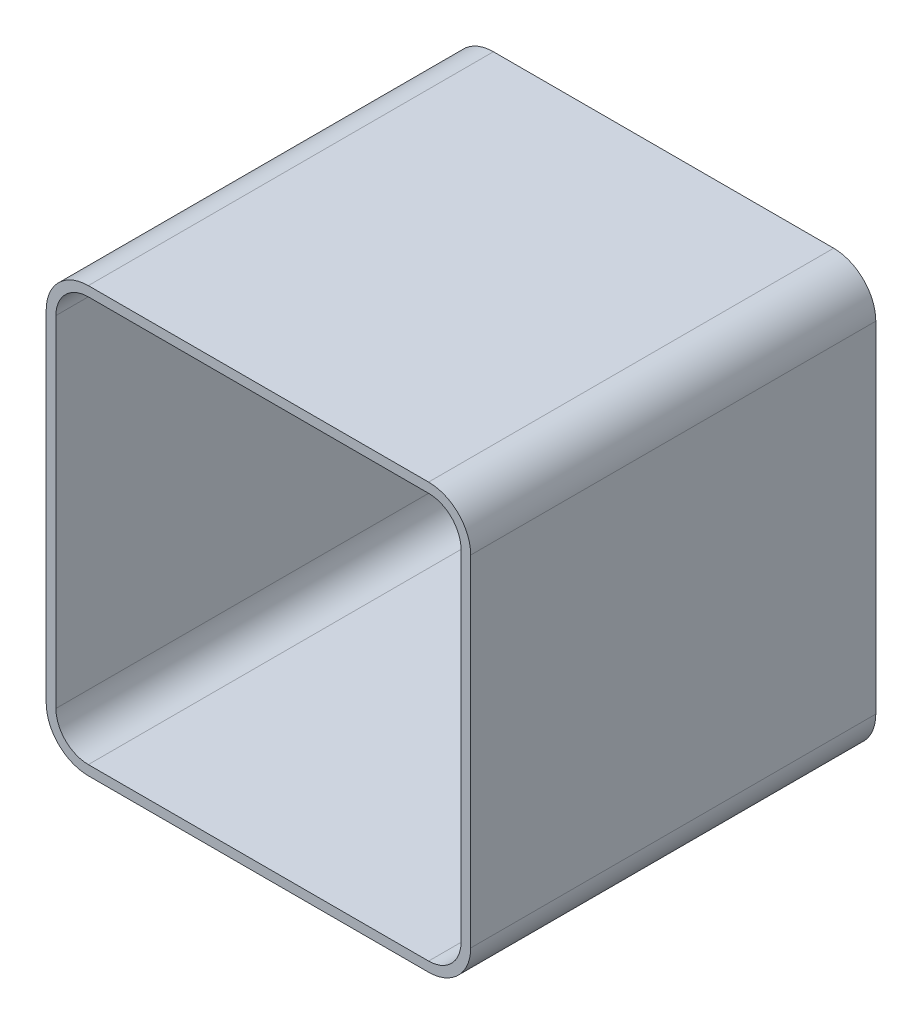
SolidWorks part; units mm, degrees
ref_plane "Front Plane" through (0, 0, 0) normal (0, 0, 1) x (1, 0, 0)
ref_plane "Top Plane" through (0, 0, 0) normal (0, 1, 0) x (1, 0, 0)
ref_plane "Right Plane" through (0, 0, 0) normal (1, 0, 0) x (0, 0, -1)
sketch "Sketch1" plane through (0, 0, 0) normal (0, 0, 1) x (1, 0, 0)
  line L1 (-12.5, 12.5) -> (12.5, 12.5)
  line L2 (-12.5, 12.5) -> (-12.5, -12.5)
  line L3 (-12.5, -12.5) -> (12.5, -12.5)
  line L4 (12.5, 12.5) -> (12.5, -12.5)
  line L5 (-12.5, 12.5) -> (12.5, -12.5) construction
  line L6 (-12.5, -12.5) -> (12.5, 12.5) construction
  line L7 (-13.1, 13.1) -> (13.1, 13.1)
  line L8 (-13.1, 13.1) -> (-13.1, -13.1)
  line L9 (-13.1, -13.1) -> (13.1, -13.1)
  line L10 (13.1, 13.1) -> (13.1, -13.1)
  line L11 (-13.1, 13.1) -> (13.1, -13.1) construction
  line L12 (-13.1, -13.1) -> (13.1, 13.1) construction
  point P0 (0, 0)
  point P7 (0, 0)
  dimension "D1" = 0.6
  dimension "D2" = 0.6
  dimension "D3" = 25
  dimension "D4" = 25
extrude "Boss-Extrude1" add sketch "Sketch1" along normal blind 25
fillet "Fillet1" radius 2 4 edges at (-12.5, -12.5, 12.5) (12.5, -12.5, 12.5) (12.5, 12.5, 12.5) (-12.5, 12.5, 12.5)
fillet "Fillet2" radius 2.6 4 edges at (13.1, -13.1, 12.5) (13.1, 13.1, 12.5) (-13.1, -13.1, 12.5) (-13.1, 13.1, 12.5)
